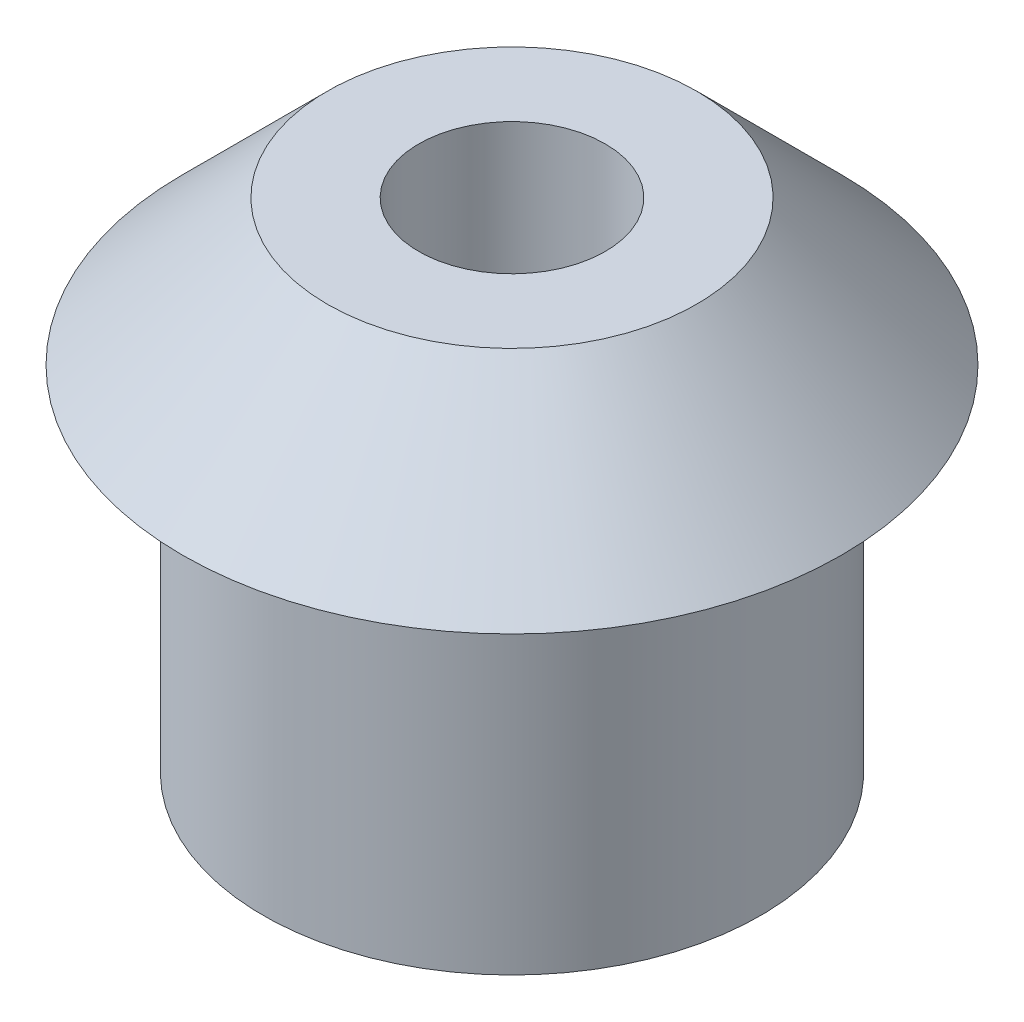
SolidWorks part; units mm, degrees
ref_plane "前视基准面" through (0, 0, 0) normal (0, 0, 1) x (1, 0, 0)
ref_plane "上视基准面" through (0, 0, 0) normal (0, 1, 0) x (1, 0, 0)
ref_plane "右视基准面" through (0, 0, 0) normal (1, 0, 0) x (0, 0, -1)
sketch "草图1" plane through (0, 0, 0) normal (0, 1, 0) x (1, 0, 0)
  circle A0 centre (0, 0) radius 4
  circle A1 centre (0, 0) radius 1.5
extrude "凸台-拉伸1" add sketch "草图1" along normal blind 5.67
sketch "草图2" plane through (0, 0, 0) normal (0, 0, 1) x (1, 0, 0)
  line L0 (0, 5.67) -> (5.3, 5.67)
  line L1 (4, 5.67) -> (-4, 5.67) construction
  line L2 (0, 5.67) -> (0, 8)
  line L3 (5.3, 5.67) -> (2.97, 8)
  line L4 (0, 8) -> (2.97, 8)
revolve "旋转1" add sketch "草图2" angle 360 about L2
sketch "草图3" plane through (0, 8, 0) normal (0, 1, 0) x (1, 0, 0)
  circle A0 centre (0, 0) radius 1.5
extrude "切除-拉伸1" cut sketch "草图3" against normal through all
